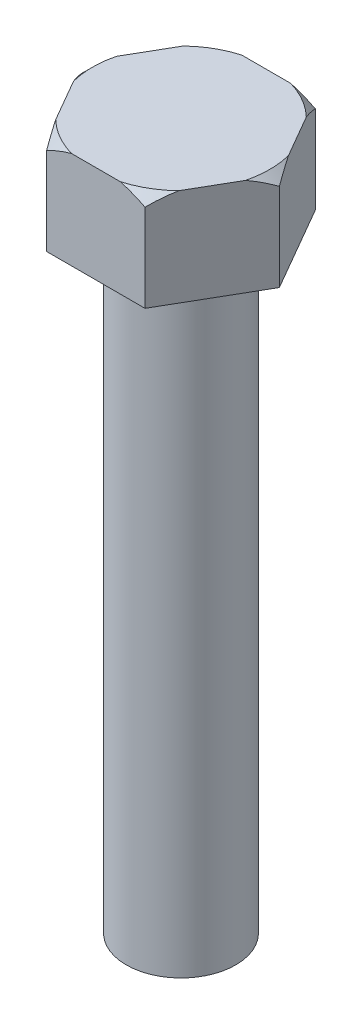
SolidWorks part; units mm, degrees
ref_plane "Front Plane" through (0, 0, 0) normal (0, 0, 1) x (1, 0, 0)
ref_plane "Top Plane" through (0, 0, 0) normal (0, 1, 0) x (1, 0, 0)
ref_plane "Right Plane" through (0, 0, 0) normal (1, 0, 0) x (0, 0, -1)
sketch "Sketch1" plane through (0, 0, 0) normal (0, 1, 0) x (1, 0, 0)
  circle A0 centre (0, 0) radius 2.25
  dimension "D1" = 4.5
extrude "Boss-Extrude1" add sketch "Sketch1" along normal blind 25
sketch "Sketch2" plane through (0, 25, 0) normal (0, 1, 0) x (1, 0, 0)
  line L0 (-4.0415, 0) -> (4.0415, 0)
  line L1 (2.0207, 3.5) -> (-2.0207, 3.5)
  line L2 (-2.0207, 3.5) -> (-4.0415, 0)
  line L3 (-4.0415, 0) -> (-2.0207, -3.5)
  line L4 (-2.0207, -3.5) -> (2.0207, -3.5)
  line L5 (2.0207, -3.5) -> (4.0415, 0)
  line L6 (4.0415, 0) -> (2.0207, 3.5)
  circle A0 centre (0, 0) radius 3.5 construction
  circle M8 centre (0, 0) radius 2.25
  dimension "D1" = 7
extrude "Boss-Extrude2" add sketch "Sketch2" along normal blind 4 contours L0 L6 L1 L2 M8 | L4 L5 L0 L3 M8 | L0 M8 | L0 M8
sketch "Sketch5" plane through (0, 0, 0) normal (0, 0, 1) x (1, 0, 0)
  line L0 (0, 29) -> (0, 0) construction
  line L1 (-2.0207, 29) -> (2.0207, 29) construction
  line L7 (3.6415, 29) -> (4.0415, 29)
  line L8 (2.0207, 29) -> (4.0415, 29) construction
  line L9 (4.0415, 29) -> (4.0415, 28.6)
  line L10 (4.0415, 29) -> (4.0415, 25) construction
  line L11 (4.0415, 28.6) -> (3.6415, 29)
  dimension "D1" = 0.4
revolve "Cut-Revolve1" cut sketch "Sketch5" angle 360 about L0
